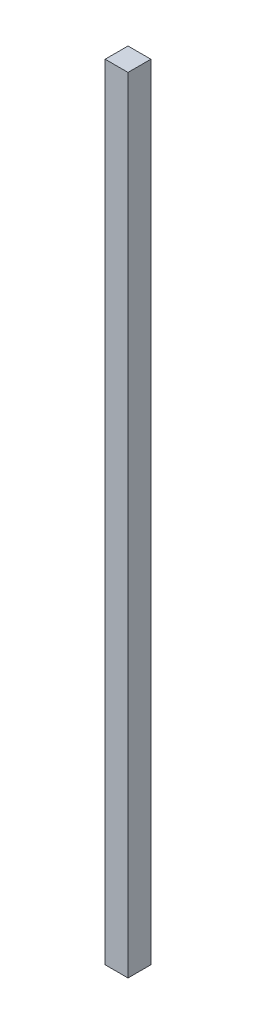
SolidWorks part; units mm, degrees
material "Oak"
ref_plane "Front Plane" through (0, 0, 0) normal (0, 0, 1) x (1, 0, 0)
ref_plane "Top Plane" through (0, 0, 0) normal (0, 1, 0) x (1, 0, 0)
ref_plane "Right Plane" through (0, 0, 0) normal (1, 0, 0) x (0, 0, -1)
sketch "Sketch1" plane through (0, 0, 0) normal (0, 0, 1) x (1, 0, 0)
  line L1 (-44.45, -1524) -> (44.45, -1524)
  line L2 (-44.45, -1524) -> (-44.45, 1524)
  line L3 (-44.45, 1524) -> (44.45, 1524)
  line L4 (44.45, -1524) -> (44.45, 1524)
  line L5 (-44.45, -1524) -> (44.45, 1524) construction
  line L6 (-44.45, 1524) -> (44.45, -1524) construction
  point P0 (0, 0)
  dimension "D1" = 3048
  dimension "D2" = 88.9
extrude "Boss-Extrude1" add sketch "Sketch1" along normal blind 88.9
